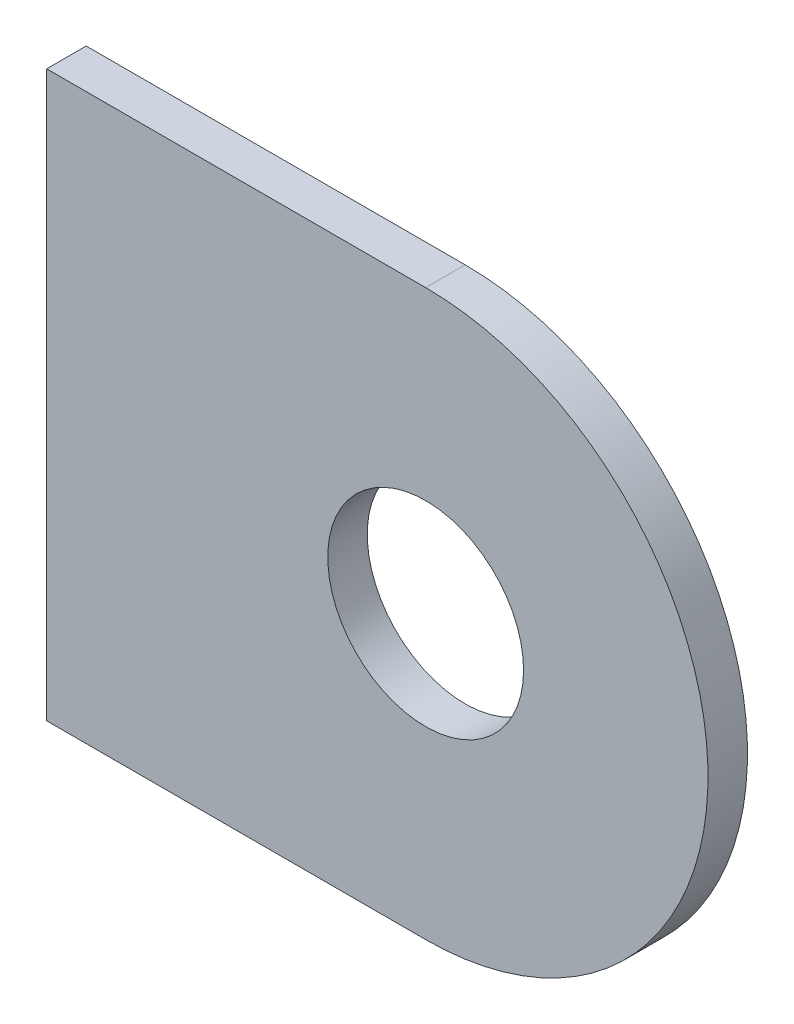
SolidWorks part; units mm, degrees
ref_plane "Front Plane" through (0, 0, 0) normal (0, 0, 1) x (1, 0, 0)
ref_plane "Top Plane" through (0, 0, 0) normal (0, 1, 0) x (1, 0, 0)
ref_plane "Right Plane" through (0, 0, 0) normal (1, 0, 0) x (0, 0, -1)
sketch "Sketch2" plane through (0, 0, 0) normal (0, 0, 1) x (1, 0, 0)
  line L1 (0, 0) -> (15.24, 0)
  line L2 (0, 0) -> (0, 22.7076)
  line L3 (0, 22.7076) -> (15.24, 22.7076)
  arc A0 (15.24, 0) -> (15.24, 22.7076) centre (15.24, 11.3538) ccw
  circle A1 centre (15.24, 11.3538) radius 3.937
  dimension "D3" = 7.874
  dimension "D1" = 15.24
  dimension "D2" = 22.7076
extrude "Boss-Extrude1" add sketch "Sketch2" along normal blind 1.5875
ref_plane "Plane1" through (0, 11.3538, 0) normal (0, -1, 0) x (-1, 0, 0)
sketch "Sketch3" plane through (0, 11.3538, 0) normal (0, -1, 0) x (-1, 0, 0)
  line L0 (-19.177, -1.5875) -> (-11.303, -1.5875) construction
  line L1 (-19.177, -1.5875) -> (-11.303, -1.5875) construction
  line L2 (-15.24, -1.5875) -> (-15.24, 11.1125) construction
  dimension "D1" = 12.7
ref_point "JOINT"
